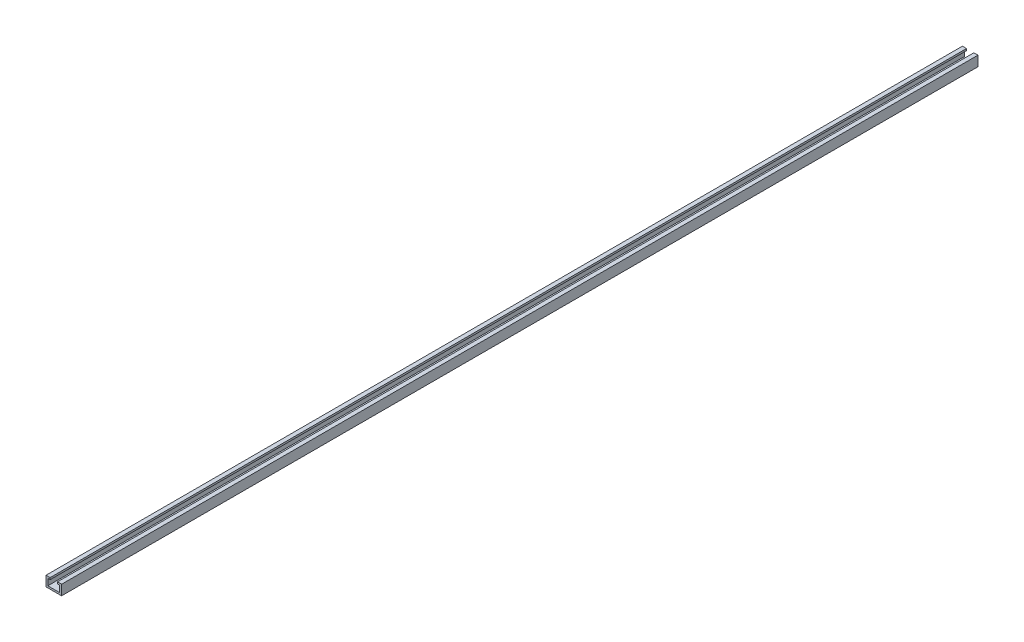
SolidWorks part; units mm, degrees
material "3.3547 (EN-AW 5083)"
ref_plane "Ebene vorne" through (0, 0, 0) normal (0, 0, 1) x (1, 0, 0)
ref_plane "Ebene oben" through (0, 0, 0) normal (0, 1, 0) x (1, 0, 0)
ref_plane "Ebene rechts" through (0, 0, 0) normal (1, 0, 0) x (0, 0, -1)
sketch "Skizze1" plane through (0, 0, 0) normal (0, 0, 1) x (1, 0, 0)
  line L0 (0, 0) -> (0, 13.4308) construction
  line L1 (-8.5, 0) -> (8.5, 0)
  line L2 (8.5, 0) -> (8.5, 11)
  line L3 (8.5, 11) -> (4, 11)
  line L4 (4, 11) -> (4, 9)
  line L5 (4, 9) -> (6.5, 9)
  line L6 (6.5, 9) -> (6.5, 2)
  line L7 (6.5, 2) -> (-6.5, 2)
  line L8 (-6.5, 9) -> (-6.5, 2)
  line L9 (-4, 9) -> (-6.5, 9)
  line L10 (-4, 11) -> (-4, 9)
  line L11 (-8.5, 11) -> (-4, 11)
  line L12 (-8.5, 0) -> (-8.5, 11)
  point P11 (0, 2)
  dimension "D1" = 17
  dimension "D2" = 11
  dimension "D3" = 8
  dimension "D4" = 2
  dimension "D5" = 7
  dimension "D6" = 13
extrude "Aufsatz-Linear austragen1" add sketch "Skizze1" along normal blind 1000
